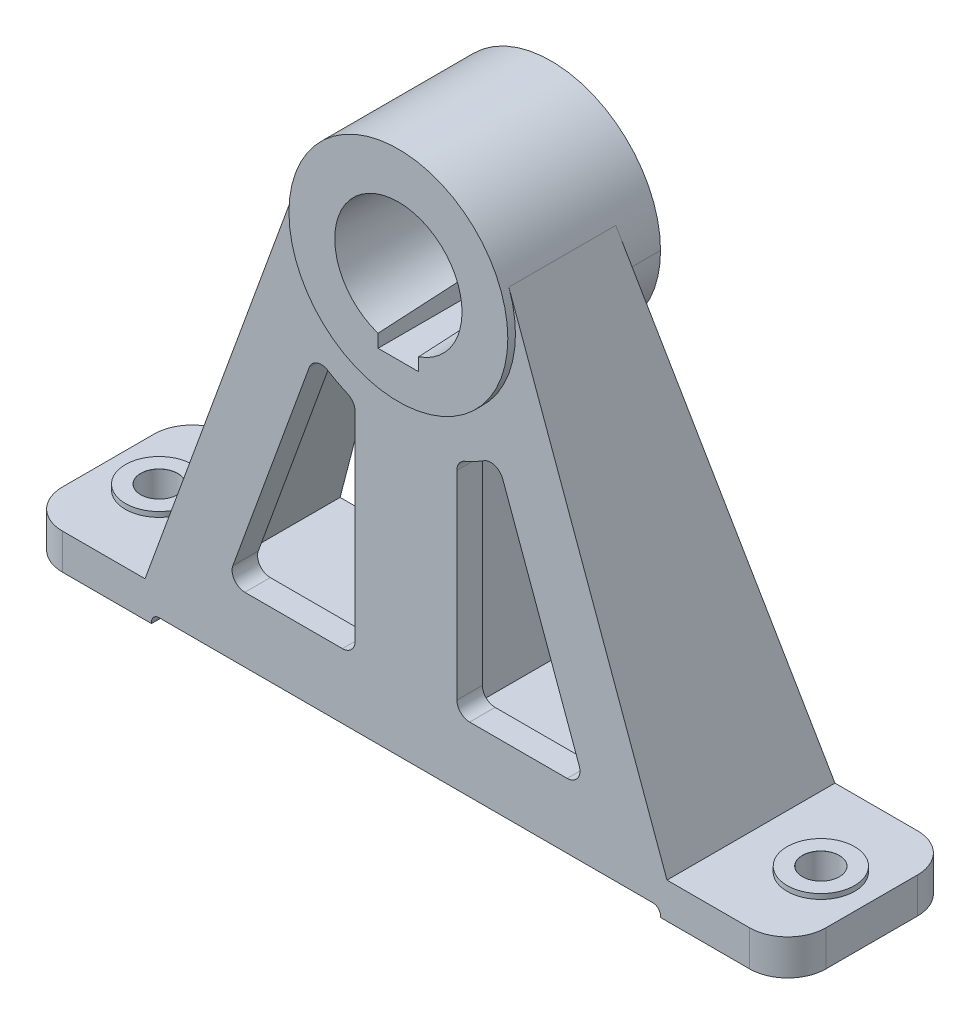
SolidWorks part; units mm, degrees
ref_plane "前视基准面" through (0, 0, 0) normal (0, 0, 1) x (1, 0, 0)
ref_plane "上视基准面" through (0, 0, 0) normal (0, 1, 0) x (1, 0, 0)
ref_plane "右视基准面" through (0, 0, 0) normal (1, 0, 0) x (0, 0, -1)
sketch "草图2" plane through (0, 0, 0) normal (0, 1, 0) x (1, 0, 0)
  line L1 (-135, -33) -> (135, -33)
  line L2 (-150, -18) -> (-150, 18)
  line L3 (-135, 33) -> (135, 33)
  line L4 (150, -18) -> (150, 18)
  line L5 (-150, -33) -> (150, 33) construction
  line L6 (-150, 33) -> (150, -33) construction
  arc A0 (135, -33) -> (150, -18) centre (135, -18) ccw
  arc A1 (-150, 18) -> (-135, 33) centre (-135, 18) cw
  arc A2 (-135, -33) -> (-150, -18) centre (-135, -18) cw
  arc A3 (135, 33) -> (150, 18) centre (135, 18) cw
  point P0 (0, 0)
  dimension "D3" = 15
  dimension "D1" = 66
  dimension "D2" = 300
extrude "凸台-拉伸1" add sketch "草图2" along normal blind 14
sketch "草图3" plane through (0, 0, 33) normal (0, 0, 1) x (1, 0, 0)
  line L0 (-100, 0) -> (100, 0)
  point P0 (0, 0)
  point P4 (0, 0)
  dimension "D1" = 200
extrude "切除-拉伸-薄壁1" cut sketch "草图3" against normal through all and the other way through all thin thin type one direction reverse wall 3.5
fillet "圆角1" radius 3 2 edges at (100, 3.5, 0) (-100, 3.5, 0)
sketch "草图5" plane through (0, 0, 0) normal (1, 0, 0) x (0, 0, -1)
  line L0 (33, 14) -> (20.0928, 105.8397)
  line L1 (-33, 14) -> (-33, 0) construction
  dimension "D1" = 8
surface "曲面-拉伸1" sketch "草图5"
sketch "草图7" plane through (0, 0, -33) normal (0, 0, 1) x (1, 0, 0)
  line L0 (0, -36.3) -> (0, 36.3) construction
  line L1 (36.3, 0) -> (-36.3, 0) construction
  circle A0 centre (0, 170) radius 43
  dimension "D1" = 86
  dimension "D2" = 170
extrude "凸台-拉伸2" add sketch "草图7" against normal blind 60 from offset 69 separate body
sketch "草图9" plane through (0, 0, 33) normal (0, 0, 1) x (1, 0, 0)
  line L0 (-102.539, 14) -> (-40.4068, 184.7069)
  line L1 (-135, 14) -> (135, 14) construction
  line L2 (37.95, 0) -> (-37.95, 0) construction
  line L3 (0, 14) -> (0, 125.5233) construction
  line L4 (135, 14) -> (-135, 14) construction
  line L5 (0, -37.95) -> (0, 37.95) construction
  line L6 (102.539, 14) -> (40.4068, 184.7069)
  line L7 (-102.539, 14) -> (102.539, 14)
  circle A0 centre (0, 170) radius 43 construction
  arc A1 (40.4068, 184.7069) -> (-40.4068, 184.7069) centre (0, 170) ccw construction
  circle A2 centre (0, 170) radius 43
  arc A3 (-40.4068, 184.7069) -> (40.4068, 184.7069) centre (0, 170) ccw
  dimension "D1" = 110
  dimension "D2" = 0
extrude "凸台-拉伸3" add sketch "草图9" against normal up to surface (42.0087 mm away)
sketch "草图10" plane through (0, 0, -33) normal (0, 0, -1) x (-1, 0, 0)
  line L3 (102.539, 14) -> (-102.539, 14) construction
  line L4 (91.8972, 14) -> (-91.8972, 14)
  line L5 (-91.8972, 14) -> (-102.539, 14) construction
  line L6 (-88.2575, 24) -> (88.2575, 24)
  line L7 (88.2575, 24) -> (45.1944, 142.3149)
  line L8 (-45.1944, 142.3149) -> (-88.2575, 24)
  line L9 (-88.2575, 24) -> (88.2575, 24) construction
  line L10 (91.8972, 14) -> (40.4387, 155.3811)
  line L11 (-40.4387, 155.3811) -> (-91.8972, 14)
  line L12 (102.539, 14) -> (91.8972, 14) construction
  arc A1 (40.4387, 155.3811) -> (-40.4387, 155.3811) centre (0, 170) ccw construction
  arc A2 (-45.1944, 142.3149) -> (45.1944, 142.3149) centre (0, 170) ccw
  circle A4 centre (0, 170) radius 43
  arc A5 (-40.4387, 155.3811) -> (40.4387, 155.3811) centre (0, 170) ccw
  dimension "D2" = 0
  dimension "D1" = 10
extrude "切除-拉伸1" cut sketch "草图10" against normal offset from surface (56 mm away) 10 up to face at (0, 26.925, 33)
sketch "草图11" plane through (0, 0, 0) normal (1, 0, 0) x (0, 0, -1)
  line L0 (24, 127) -> (33, 14)
  line L1 (24, 127) -> (24, 213) construction
  line L2 (-23, 127) -> (24, 127) construction
rib "筋1" sketch "草图11" sketch "草图11" thickness 10 extrusion direction parallel to sketch draft on no parameters "D1"=10
sketch "草图12" plane through (0, 0, 23) normal (0, 0, -1) x (-1, 0, 0)
  line L6 (20, 115.5574) -> (20, 29)
  line L7 (20, 29) -> (70.475, 29)
  line L8 (70.475, 29) -> (35.7722, 124.3453)
  line L9 (20, 112.1727) -> (20, 34)
  line L10 (25, 29) -> (63.3343, 29)
  line L11 (68.0327, 35.7101) -> (37.998, 118.2298)
  arc A1 (63.3343, 29) -> (68.0327, 35.7101) centre (63.3343, 34) ccw
  arc A2 (20, 115.5574) -> (35.7722, 124.3453) centre (0, 170) ccw
  arc A3 (23.0159, 116.7621) -> (30.6567, 120.7642) centre (0, 170) ccw
  arc A4 (20, 34) -> (25, 29) centre (25, 34) ccw
  arc A5 (23.0159, 116.7621) -> (20, 112.1727) centre (25, 112.1727) ccw
  arc A6 (30.6567, 120.7642) -> (37.998, 118.2298) centre (33.2995, 116.5197) cw
  dimension "D2" = 5
  dimension "D3" = 5
  dimension "D1" = 15
extrude "切除-拉伸2" cut sketch "草图12" against normal through all
mirror "镜向1" about plane through (0, 0, 0) normal (1, 0, 0) of "切除-拉伸2"
sketch "草图13" plane through (0, 0, 36) normal (0, 0, 1) x (1, 0, 0)
  circle A0 centre (0, 170) radius 25
  dimension "D1" = 50
extrude "切除-拉伸3" cut sketch "草图13" against normal through all draft 3
sketch "草图14" plane through (0, 0, 36) normal (0, 0, 1) x (1, 0, 0)
  line L0 (0, 141.2) -> (0, 170)
  line L1 (0, -37.95) -> (0, 37.95) construction
  circle A2 centre (0, 170) radius 25 construction
  dimension "D1" = 53.8
extrude "切除-拉伸-薄壁2" cut sketch "草图14" against normal through all and the other way through all thin thin type mid plane wall 16
sketch "草图15" plane through (0, 14, 0) normal (0, 1, 0) x (1, 0, 0)
  line L0 (-117.15, 0) -> (117.15, 0) construction
  line L1 (135, 33) -> (102.539, 33) construction
  point P0 (130, 0)
  point P7 (72.4479, -84.0863)
  dimension "D1" = 33
  dimension "D2" = 130
sketch "草图16" plane through (0, 14, 0) normal (0, 1, 0) x (1, 0, 0)
  circle A0 centre (130, 0) radius 13.25
  dimension "D1" = 26.5
extrude "凸台-拉伸4" add sketch "草图16" along normal blind 2
hole_wizard "Ø14.5 (14.5) 直径孔1" positions "草图17" profile "草图18" hole size "Ø14.5" standard "GB" end condition up to next
sketch "草图17" plane through (0, 16, 0) normal (0, 1, 0) x (1, 0, 0)
  point P0 (130, 0)
sketch "草图18" plane through (130, 16, 0) normal (1, 0, 0) x (0, 0, 1)
  line L0 (0, 0) -> (0, 16)
  line L1 (0, 16) -> (7.25, 16)
  line L2 (7.25, 16) -> (7.25, 0.025)
  line L3 (7.25, 0.025) -> (7.275, 0)
  line L5 (7.275, 0) -> (0, 0)
  line L6 (-7.25, 0.025) -> (-7.275, 0) construction
  line L11 (0, -6.35) -> (0, 107.95) construction
  dimension "通孔孔直径" = 14.5
  dimension "通孔孔深度" = 16
  dimension "近端锥形沉头孔直径" = 14.55
  dimension "近端锥形沉头孔角度" = 90
mirror "镜向2" about plane through (0, 0, 0) normal (1, 0, 0) of "凸台-拉伸4", "Ø14.5 (14.5) 直径孔1"
